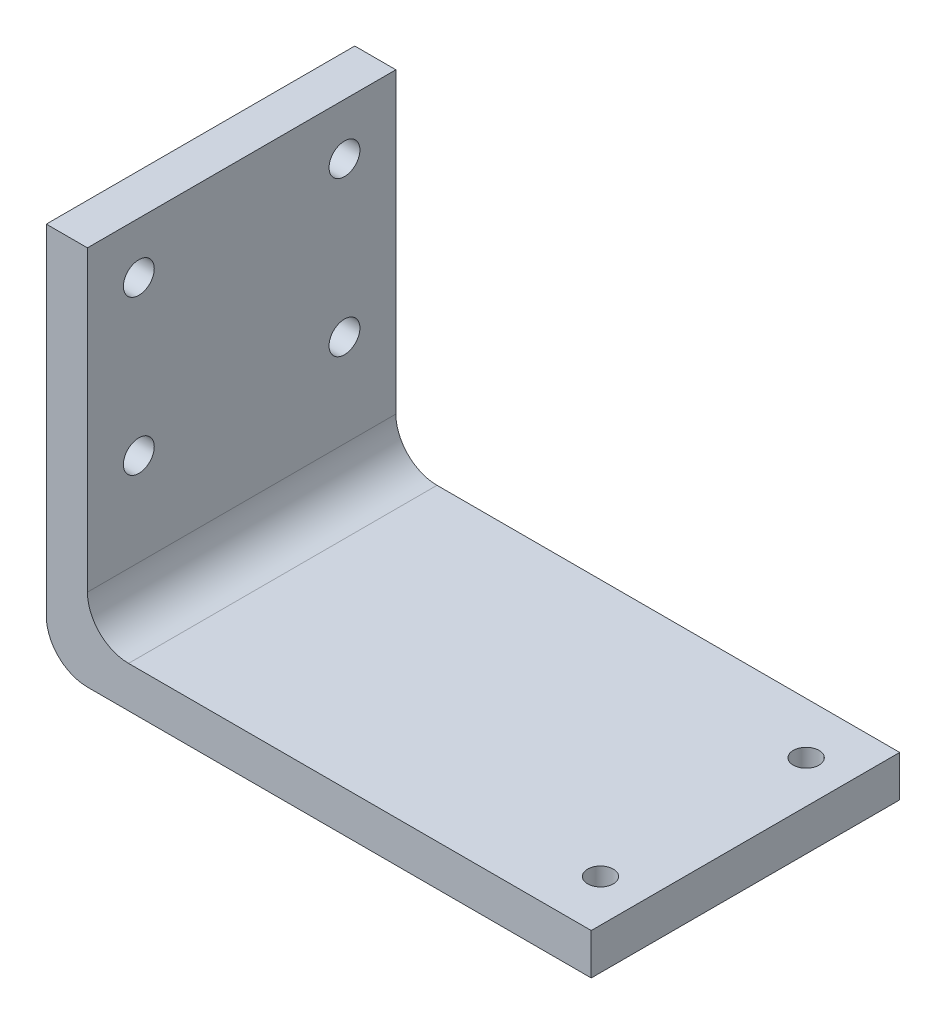
SolidWorks part; units mm, degrees
ref_plane "Front Plane" through (0, 0, 0) normal (0, 0, 1) x (1, 0, 0)
ref_plane "Top Plane" through (0, 0, 0) normal (0, 1, 0) x (1, 0, 0)
ref_plane "Right Plane" through (0, 0, 0) normal (1, 0, 0) x (0, 0, -1)
sketch "Sketch1" plane through (0, 0, 0) normal (0, 0, 1) x (1, 0, 0)
  line L1 (5.08, 0) -> (67.31, 0)
  line L3 (10.16, 5.08) -> (67.31, 5.08)
  line L4 (67.31, 0) -> (67.31, 5.08)
  line L6 (0, 5.08) -> (0, 46.99)
  line L7 (0, 46.99) -> (5.08, 46.99)
  line L8 (5.08, 10.16) -> (5.08, 46.99)
  arc A0 (10.16, 5.08) -> (5.08, 10.16) centre (10.16, 10.16) cw
  arc A1 (0, 5.08) -> (5.08, 0) centre (5.08, 5.08) ccw
  dimension "D5" = 5.08
  dimension "D1" = 5.08
  dimension "D3" = 5.08
  dimension "D4" = 5.08
extrude "Boss-Extrude1" add sketch "Sketch1" along normal blind 38.1
hole_wizard "1/8 (0.125) Diameter Hole1" positions "Sketch2" profile "Sketch3" hole size "1/8" standard "ANSI Inch"
sketch "Sketch2" plane through (0, 5.08, 0) normal (0, 1, 0) x (1, 0, 0)
  line L0 (0, -38.1) -> (0, 0) construction
  line L1 (67.31, -38.1) -> (10.16, -38.1) construction
  point P0 (62.103, -31.75)
  point P2 (62.103, -6.35)
  dimension "D1" = 62.103
  dimension "D2" = 25.4
  dimension "D3" = 6.35
sketch "Sketch3" plane through (62.103, 5.08, 31.75) normal (1, 0, 0) x (0, 0, 1)
  line L0 (0, 0) -> (0, 6.0339)
  line L1 (0, 6.0339) -> (1.5875, 5.08)
  line L2 (1.5875, 5.08) -> (1.5875, 0)
  line L5 (1.5875, 0) -> (0, 0)
  line L10 (0, 6.0339) -> (-1.5875, 5.08) construction
  line L11 (0, -6.35) -> (0, 107.95) construction
  dimension "Hole Dia." = 3.175
  dimension "Hole Depth" = 5.08
  dimension "Drill Angle" = 118
hole_wizard "1/8 (0.15) Diameter Hole1" positions "Sketch4" profile "Sketch5" hole size "1/8" standard "ANSI Inch"
sketch "Sketch4" plane through (5.08, 0, 0) normal (1, 0, 0) x (0, 0, -1)
  line L0 (-38.1, 10.16) -> (-38.1, 46.99) construction
  line L1 (-38.1, 46.99) -> (0, 46.99) construction
  point P0 (-31.75, 40.64)
  point P2 (-6.35, 40.64)
  point P4 (-6.35, 21.59)
  point P6 (-31.75, 21.59)
  dimension "D1" = 6.35
  dimension "D2" = 25.4
  dimension "D3" = 6.35
  dimension "D4" = 19.05
sketch "Sketch5" plane through (5.08, 40.64, 31.75) normal (0, 1, 0) x (0, 0, -1)
  line L0 (0, 0) -> (0, 6.2246)
  line L1 (0, 6.2246) -> (1.905, 5.08)
  line L2 (1.905, 5.08) -> (1.905, 0)
  line L5 (1.905, 0) -> (0, 0)
  line L10 (0, 6.2246) -> (-1.905, 5.08) construction
  line L11 (0, -6.35) -> (0, 107.95) construction
  dimension "Hole Dia." = 3.81
  dimension "Hole Depth" = 5.08
  dimension "Drill Angle" = 118
